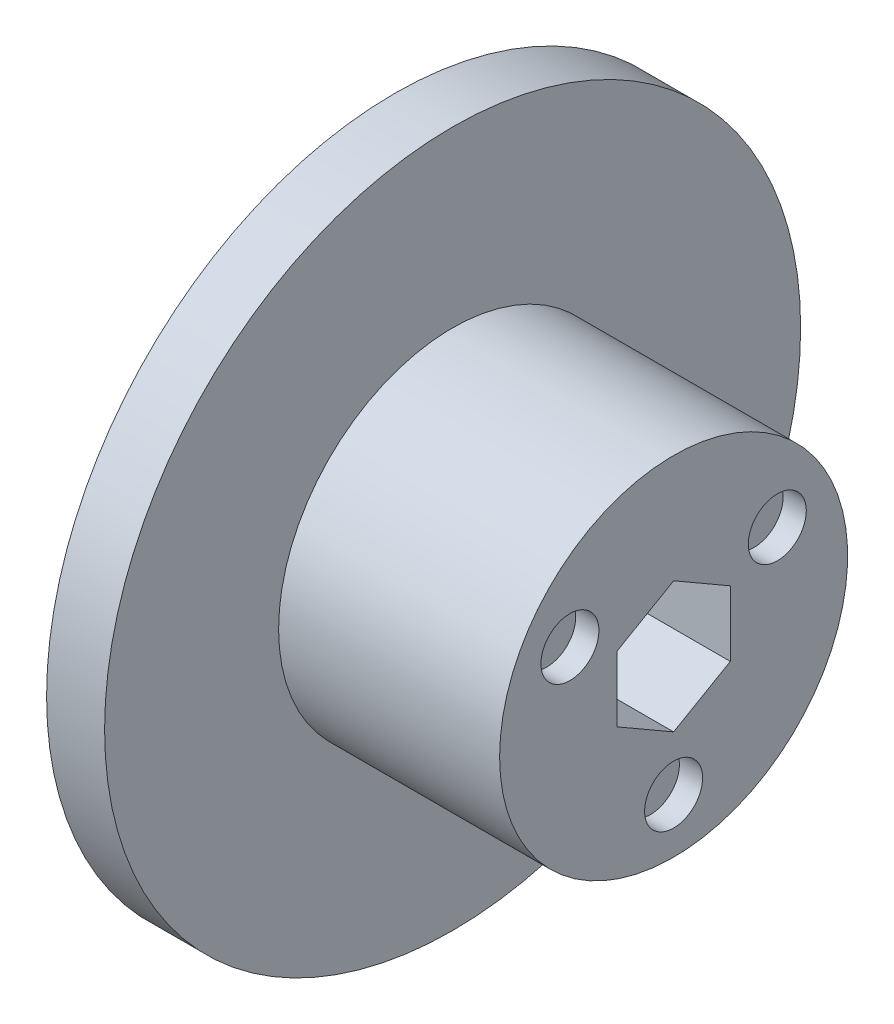
SolidWorks part; units mm, degrees
ref_plane "Front Plane" through (0, 0, 0) normal (0, 0, 1) x (1, 0, 0)
ref_plane "Top Plane" through (0, 0, 0) normal (0, 1, 0) x (1, 0, 0)
ref_plane "Right Plane" through (0, 0, 0) normal (1, 0, 0) x (0, 0, -1)
sketch "Sketch2" plane through (0, 0, 0) normal (1, 0, 0) x (0, 0, -1)
  circle A0 centre (0, 0) radius 30
  dimension "D1" = 60
extrude "Boss-Extrude1" add sketch "Sketch2" along normal blind 5
sketch "Sketch3" plane through (5, 0, 0) normal (1, 0, 0) x (0, 0, -1)
  circle A0 centre (0, 0) radius 15
  dimension "D1" = 30
extrude "Boss-Extrude2" add sketch "Sketch3" along normal blind 19.05
sketch "Sketch4" plane through (24.05, 0, 0) normal (1, 0, 0) x (0, 0, -1)
  line L1 (0, 5.6407) -> (-4.885, 2.8204)
  line L2 (-4.885, 2.8204) -> (-4.885, -2.8204)
  line L3 (-4.885, -2.8204) -> (0, -5.6407)
  line L4 (0, -5.6407) -> (4.885, -2.8204)
  line L5 (4.885, -2.8204) -> (4.885, 2.8204)
  line L6 (4.885, 2.8204) -> (0, 5.6407)
  circle A0 centre (0, 0) radius 4.885 construction
  dimension "D1" = 9.77
extrude "Cut-Extrude1" cut sketch "Sketch4" against normal up to surface (24.05 mm away) up to face at (0, 0, -30)
sketch "Sketch5" plane through (24.05, 0, 0) normal (1, 0, 0) x (0, 0, -1)
  line L0 (0, -5.6407) -> (0, -15) construction
  line L1 (4.885, 2.8204) -> (12.9904, 7.5) construction
  line L2 (-4.885, 2.8204) -> (-12.9904, 7.5) construction
  circle A1 centre (0, 0) radius 15 construction
  circle A2 centre (8.9377, 5.1602) radius 2.5
  circle A3 centre (-8.9377, 5.1602) radius 2.5
  circle A4 centre (0, -10.3204) radius 2.5
  dimension "D1" = 5
  dimension "D2" = 5
  dimension "D3" = 5
extrude "Cut-Extrude2" cut sketch "Sketch5" against normal blind 2
